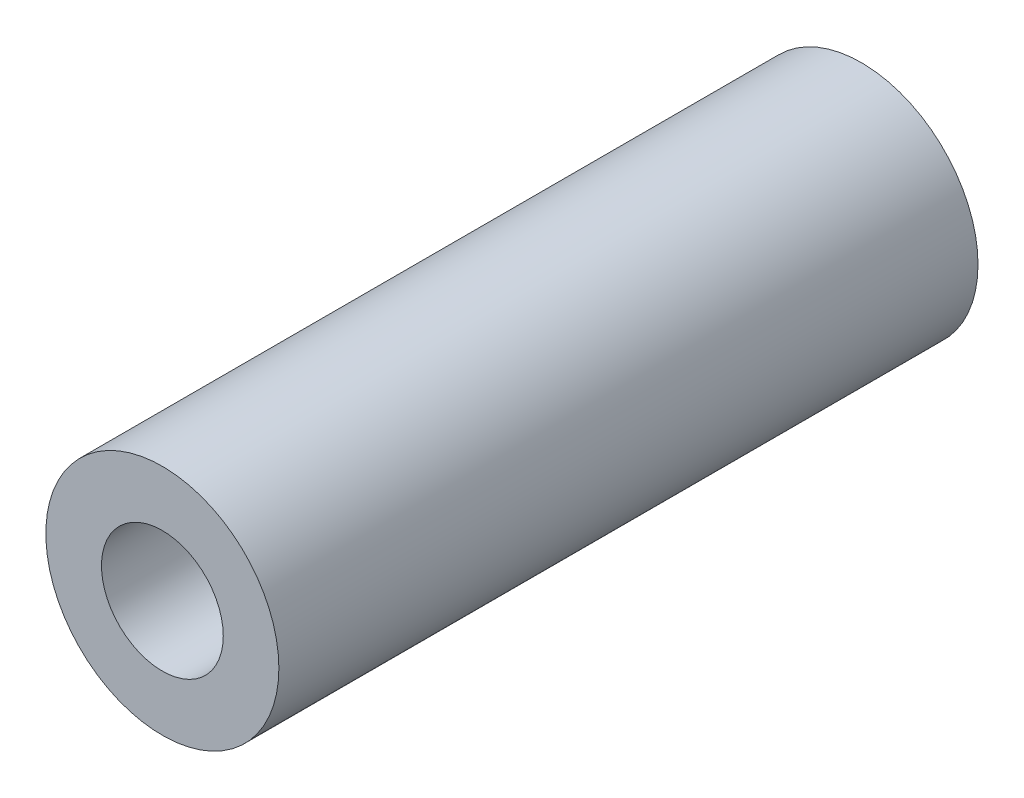
SolidWorks part; units mm, degrees
material "6061-T6 (SS)"
ref_plane "Front Plane" through (0, 0, 0) normal (0, 0, 1) x (1, 0, 0)
ref_plane "Top Plane" through (0, 0, 0) normal (0, 1, 0) x (1, 0, 0)
ref_plane "Right Plane" through (0, 0, 0) normal (1, 0, 0) x (0, 0, -1)
sketch "Sketch1" plane through (0, 0, 0) normal (0, 0, 1) x (1, 0, 0)
  circle A0 centre (0, 0) radius 4.7625
  circle A1 centre (0, 0) radius 2.4892
  dimension "D1" = 4.9784
  dimension "D2" = 9.525
extrude "Boss-Extrude1" add sketch "Sketch1" along normal blind 28.575
